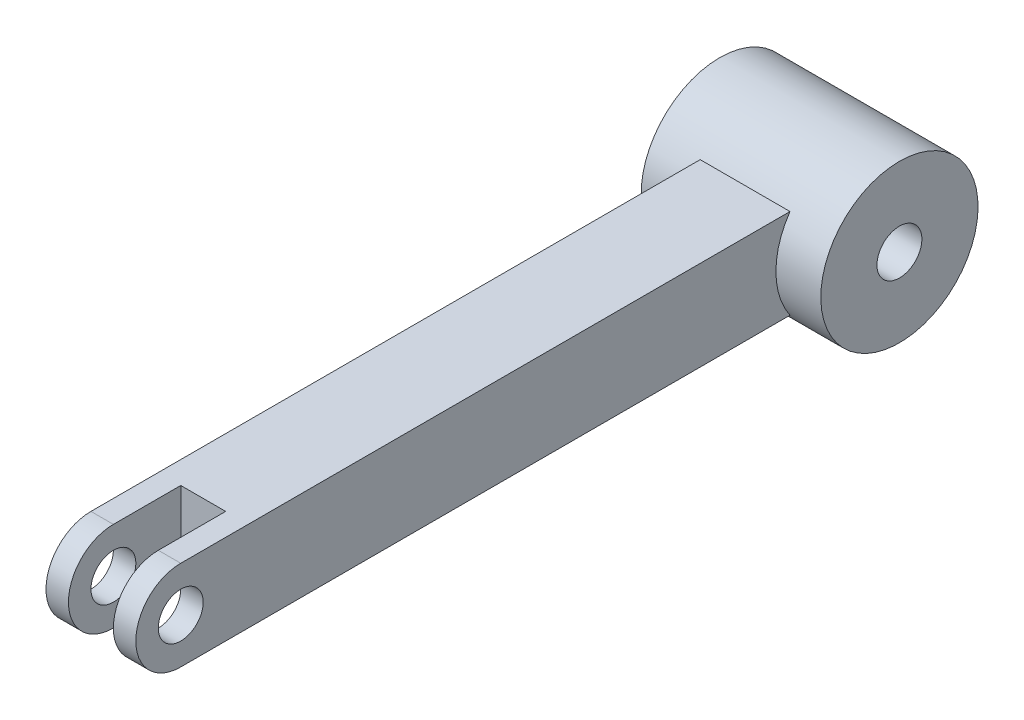
SolidWorks part; units mm, degrees
ref_plane "Front Plane" through (0, 0, 0) normal (0, 0, 1) x (1, 0, 0)
ref_plane "Top Plane" through (0, 0, 0) normal (0, 1, 0) x (1, 0, 0)
ref_plane "Right Plane" through (0, 0, 0) normal (1, 0, 0) x (0, 0, -1)
sketch "Sketch1" plane through (0, 0, 0) normal (0, 0, 1) x (1, 0, 0)
  line L1 (2, 2) -> (-2, 2)
  line L2 (2, 2) -> (2, -2)
  line L3 (2, -2) -> (-2, -2)
  line L4 (-2, 2) -> (-2, -2)
  line L5 (2, 2) -> (-2, -2) construction
  line L6 (2, -2) -> (-2, 2) construction
  point P0 (0, 0)
  dimension "D1" = 4
  dimension "D2" = 4
extrude "Boss-Extrude1" add sketch "Sketch1" along normal blind 30
sketch "Sketch2" plane through (2, 0, 0) normal (1, 0, 0) x (0, 0, -1)
  line L0 (-30, -2) -> (-30, 2) construction
  circle A0 centre (-30, 0) radius 2
  circle A1 centre (-30, 0) radius 1
  dimension "D1" = 2
  dimension "D2" = 4
extrude "Boss-Extrude2" add sketch "Sketch2" against normal blind 4
sketch "Sketch3" plane through (2, 0, 0) normal (1, 0, 0) x (0, 0, -1)
  line L0 (-30, -1) -> (-30, 1) construction
  circle A0 centre (-30, 0) radius 1
extrude "Cut-Extrude1" cut sketch "Sketch3" against normal through all
sketch "Sketch4" plane through (2, 0, 0) normal (1, 0, 0) x (0, 0, -1)
  circle A0 centre (0, 0) radius 3.5
  circle A1 centre (0, 0) radius 1
  dimension "D1" = 7
  dimension "D2" = 2
extrude "Boss-Extrude3" add sketch "Sketch4" along normal blind 2 and the other way blind 6
sketch "Sketch5" plane through (4, 0, 0) normal (1, 0, 0) x (0, 0, -1)
  circle A0 centre (0, 0) radius 1 construction
  circle A1 centre (0, 0) radius 1
extrude "Cut-Extrude2" cut sketch "Sketch5" against normal through all
ref_plane "Plane1" through (0, 0, 29) normal (0, 0, 1) x (1, 0, 0)
sketch "Sketch6" plane through (0, 0, 29) normal (0, 0, 1) x (1, 0, 0)
  line L1 (2, 2.5) -> (-2, 2.5) construction
  line L2 (1, 2.5) -> (1, -2.5)
  line L3 (1, -2.5) -> (-1, -2.5)
  line L4 (-1, 2.5) -> (-1, -2.5)
  line L5 (1, 2.5) -> (-1, -2.5) construction
  line L6 (1, -2.5) -> (-1, 2.5) construction
  line L8 (0, 2.5) -> (0, 0) construction
  line L11 (-1, 2.5) -> (1, 2.5)
  point P4 (0, 0)
  dimension "D1" = 2
extrude "Cut-Extrude3" cut sketch "Sketch6" along normal blind 10 and the other way blind 2
